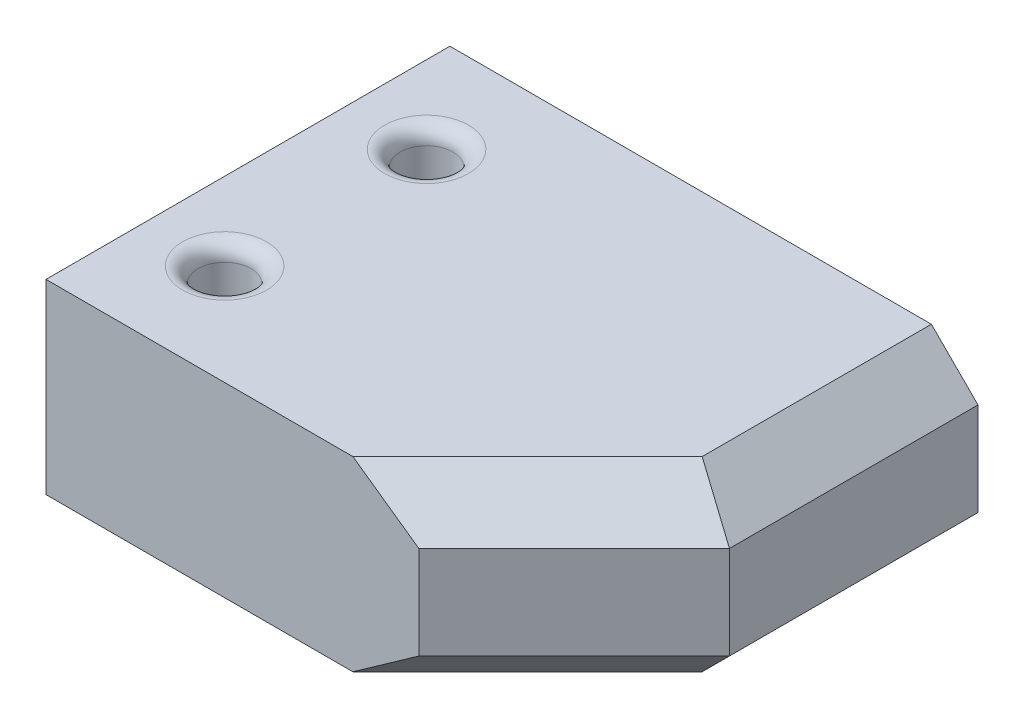
SolidWorks part; units mm, degrees
ref_plane "Front Plane" through (0, 0, 0) normal (0, 0, 1) x (1, 0, 0)
ref_plane "Top Plane" through (0, 0, 0) normal (0, 1, 0) x (1, 0, 0)
ref_plane "Right Plane" through (0, 0, 0) normal (1, 0, 0) x (0, 0, -1)
sketch "Sketch1" plane through (0, 0, 0) normal (0, 1, 0) x (1, 0, 0)
  line L0 (0, -6.5) -> (0, 6.5)
  line L1 (0, 6.5) -> (17, 6.5)
  line L2 (17, 6.5) -> (17, -6.5)
  line L3 (17, -6.5) -> (0, -6.5)
  point P4 (0, 0)
  dimension "D1" = 17
  dimension "D2" = 13
extrude "Boss-Extrude1" add sketch "Sketch1" along normal blind 6
sketch "Sketch2" plane through (0, 6, 0) normal (0, 1, 0) x (1, 0, 0)
  line L0 (2.5, 6.5) -> (2.5, -6.5) construction
  line L1 (17, 6.5) -> (0, 6.5) construction
  line L2 (0, -6.5) -> (17, -6.5) construction
  line L3 (5, 6.5) -> (5, -6.5) construction
  line L4 (0, 6.5) -> (0, -6.5) construction
  line L5 (0, 6.5) -> (5, 0) construction
  line L6 (5, 0) -> (0, -6.5) construction
  circle A0 centre (2.5, 3.25) radius 0.85
  circle A1 centre (2.5, -3.25) radius 0.85
  dimension "D3" = 1.7
  dimension "D4" = 1.7
  dimension "D1" = 2.5
  dimension "D2" = 2.5
extrude "Cut-Extrude1" cut sketch "Sketch2" against normal through all both and the other way through all
fillet "Fillet1" radius 0.5 4 edges at (2.5, 0, 4.1) (2.5, 0, -2.4) (2.5, 6, 2.4) (2.5, 6, -4.1)
chamfer "Chamfer1" distance 5 angle 45 1 edges at (17, 3, 6.5)
chamfer "Chamfer2" distance 1.5 angle 45 4 edges at (17, 0, -2.5) (14.5, 0, 4) (17, 6, -2.5) (14.5, 6, 4)
